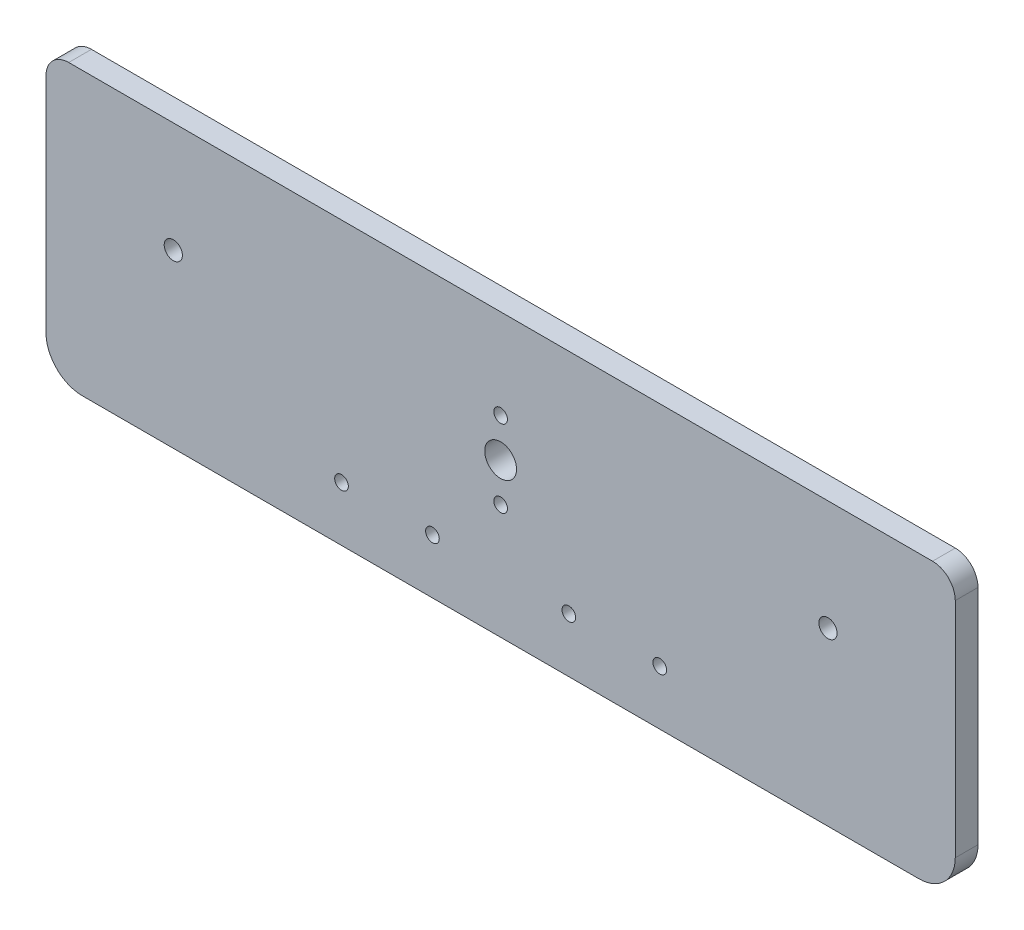
SolidWorks part; units mm, degrees
ref_plane "Alzado" through (0, 0, 0) normal (0, 0, 1) x (1, 0, 0)
ref_plane "Planta" through (0, 0, 0) normal (0, 1, 0) x (1, 0, 0)
ref_plane "Vista lateral" through (0, 0, 0) normal (1, 0, 0) x (0, 0, -1)
sketch "Croquis1" plane through (0, 0, 0) normal (0, 0, 1) x (1, 0, 0)
  line L0 (0, 0) -> (100, 0) construction
  line L1 (0, 0) -> (0, -23.25) construction
  line L2 (72, 0) -> (72, -19.25) construction
  line L3 (100, 0) -> (100, -49)
  line L4 (92, -57) -> (-92, -57)
  line L5 (0, -57) -> (0, -23.25) construction
  line L6 (0, 0) -> (0, 5) construction
  line L7 (-100, 5) -> (100, 5)
  line L8 (100, 5) -> (100, 0)
  line L9 (-100, 5) -> (-100, 0)
  line L10 (-100, 0) -> (-100, -49)
  circle A0 centre (0, -23.25) radius 3.5
  circle A1 centre (72, -19.25) radius 2
  circle A2 centre (-72, -19.25) radius 2
  circle A6 centre (-72, -19.25) radius 2
  arc A10 (100, -49) -> (92, -57) centre (92, -49) cw
  arc A11 (-100, -49) -> (-92, -57) centre (-92, -49) ccw
  circle A12 centre (15, -45) radius 1.5
  circle A13 centre (35, -45) radius 1.5
  circle A14 centre (-35, -45) radius 1.5
  circle A15 centre (-15, -45) radius 1.5
  circle A19 centre (0, -23.25) radius 5 construction
  point P34 (100, -57)
  point P37 (-100, -57)
  dimension "D4" = 7
  dimension "D5" = 4
  dimension "D13" = 8
  dimension "D14" = 3
  dimension "D15" = 3
  dimension "D1" = 19.25
  dimension "D3" = 72
  dimension "D6" = 100
  dimension "D7" = 57
  dimension "D12" = 5
  dimension "D16" = 20
  dimension "D17" = 15
  dimension "D18" = 12
extrude "Saliente-Extruir1" add sketch "Croquis1" along normal blind 5
fillet "Redondeo1" radius 5 2 edges at (100, 5, 2.5) (-100, 5, 2.5)
sketch "Croquis2" plane through (0, 0, 5) normal (0, 0, 1) x (1, 0, 0)
  line L0 (0, -31.75) -> (0, -14.75) construction
  circle A0 centre (0, -14.75) radius 1.5
  circle A1 centre (0, -31.75) radius 1.5
  circle A2 centre (0, -23.25) radius 3.5 construction
  point P7 (0, -23.25)
  dimension "D1" = 3
  dimension "D2" = 17
extrude "Cortar-Extruir1" cut sketch "Croquis2" against normal through all
